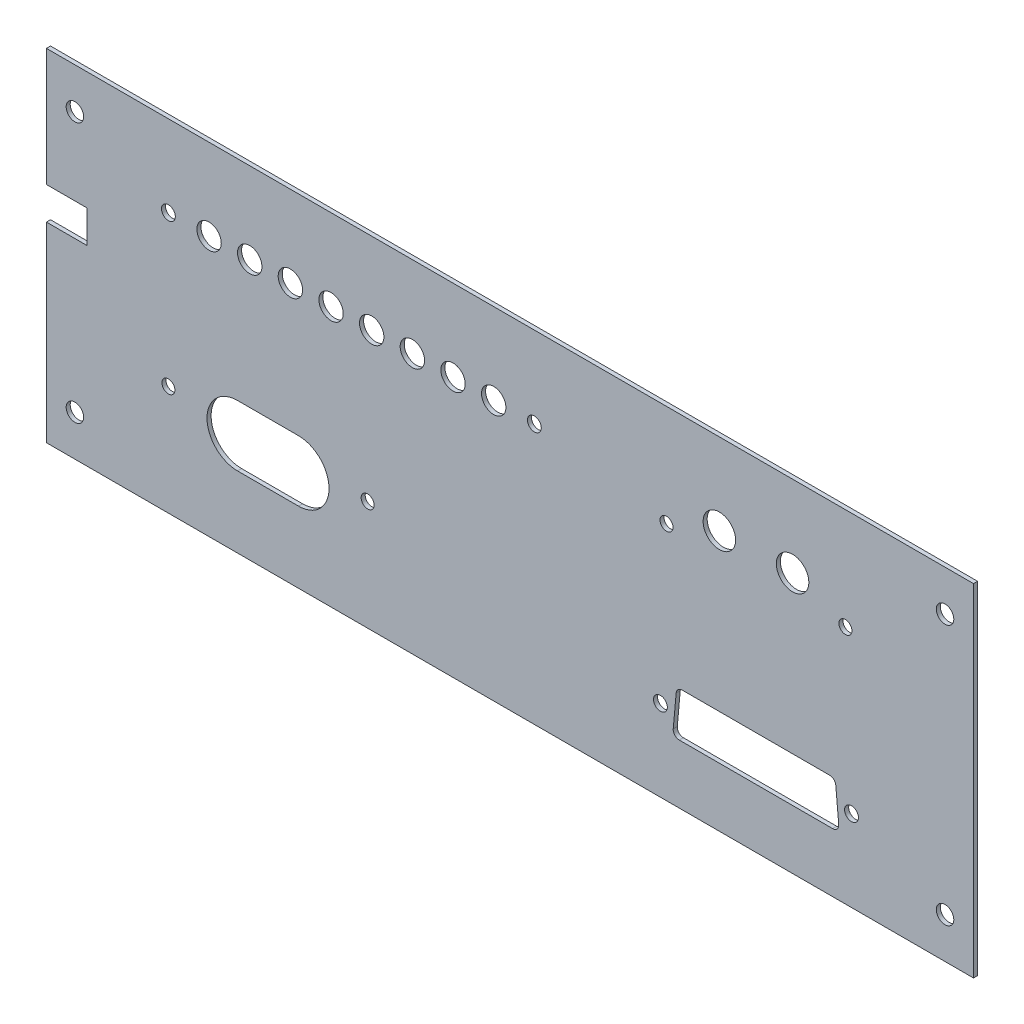
SolidWorks part; units mm, degrees
ref_plane "Спереди" through (0, 0, 0) normal (0, 0, 1) x (1, 0, 0)
ref_plane "Сверху" through (0, 0, 0) normal (0, 1, 0) x (1, 0, 0)
ref_plane "Справа" through (0, 0, 0) normal (1, 0, 0) x (0, 0, -1)
sketch "Эскиз1" plane through (0, 0, 0) normal (0, 0, 1) x (1, 0, 0)
  line L0 (0, 0) -> (58.061, 0) construction
  line L1 (0, 0) -> (0, 47.3035) construction
  line L3 (-114, -42) -> (114, -42)
  line L4 (-114, -42) -> (-114, 42)
  line L5 (-114, 42) -> (114, 42)
  line L6 (114, -42) -> (114, 42)
  circle A8 centre (107, 32) radius 2.15
  circle A9 centre (-107, 32) radius 2.15
  circle A10 centre (-107, -32) radius 2.15
  circle A11 centre (107, -32) radius 2.15
  dimension "D14" = 4.3
  dimension "D15" = 10
  dimension "D16" = 7
  dimension "D1" = 84
  dimension "D2" = 228
extrude "Вытянуть1" add sketch "Эскиз1" along normal blind 1
sketch "Эскиз3" plane through (0, 0, 1) normal (0, 0, 1) x (1, 0, 0)
  line L0 (-47.9981, -22) -> (120.6827, -22) construction
  line L1 (40.1487, -25.8642) -> (40.876, -17.8642)
  line L2 (41.6425, -27.5) -> (79.3575, -27.5)
  line L3 (-114, -42) -> (114, -42) construction
  line L4 (42.3698, -16.5) -> (78.6302, -16.5)
  line L5 (34.3104, 17) -> (86.5925, 17) construction
  line L6 (80.8513, -25.8642) -> (80.124, -17.8642)
  line L7 (60.5, 95.3032) -> (60.5, -77.6913) construction
  line L10 (51.5, 22) -> (68.5193, 22) construction
  line L11 (114, -42) -> (114, 42) construction
  line L12 (114, 42) -> (-114, 42) construction
  circle A0 centre (37, -22) radius 1.7
  circle A1 centre (84, -22) radius 1.7
  arc A2 (41.6425, -27.5) -> (40.1487, -25.8642) centre (41.6425, -26) cw
  arc A3 (42.3698, -16.5) -> (40.876, -17.8642) centre (42.3698, -18) ccw
  arc A4 (80.124, -17.8642) -> (78.6302, -16.5) centre (78.6302, -18) ccw
  arc A5 (79.3575, -27.5) -> (80.8513, -25.8642) centre (79.3575, -26) ccw
  circle A6 centre (38.5, 17) radius 1.6
  circle A7 centre (82.5, 17) radius 1.6
  circle A8 centre (51.5, 22) radius 4
  circle A9 centre (69.5, 22) radius 4
  point P14 (40, -27.5)
  point P17 (41, -16.5)
  point P20 (80, -16.5)
  point P23 (81, -27.5)
  dimension "D4" = 47
  dimension "D5" = 3.4
  dimension "D6" = 1.5
  dimension "D9" = 3.2
  dimension "D11" = 18
  dimension "D12" = 8
  dimension "D13" = 44
  dimension "D14" = 20
  dimension "D8" = 30
  dimension "D1" = 39
  dimension "D2" = 41
  dimension "D3" = 11
  dimension "D7" = 20
  dimension "D10" = 25
extrude "Вырез-Вытянуть1" cut sketch "Эскиз3" against normal blind 10
sketch "Эскиз4" plane through (0, 0, 1) normal (0, 0, 1) x (1, 0, 0)
  line L0 (-114, 42) -> (-114, -42) construction
  line L2 (-153.842, -17) -> (-33.1698, -17) construction
  line L6 (-67, -9.5) -> (-52, -9.5)
  line L7 (-67, -24.5) -> (-52, -24.5)
  line L8 (-59.5, -4.8658) -> (-59.5, -32.5755) construction
  line L9 (-108, 9) -> (-127.313, 9) construction
  line L10 (114, 42) -> (-114, 42) construction
  line L11 (-120.3986, 5) -> (-104, 5)
  line L12 (-120.3986, 5) -> (-120.3986, 13)
  line L13 (-120.3986, 13) -> (-104, 13)
  line L14 (-104, 5) -> (-104, 13)
  arc A5 (-67, -9.5) -> (-67, -24.5) centre (-67, -17) ccw
  arc A6 (-52, -9.5) -> (-52, -24.5) centre (-52, -17) cw
  circle A7 centre (-84, -15) radius 1.6
  circle A8 centre (-35, -15) radius 1.6
  dimension "D3" = 33
  dimension "D12" = 8
  dimension "D13" = 15
  dimension "D14" = 49
  dimension "D15" = 2
  dimension "D2" = 10
  dimension "D16" = 15
  dimension "D17" = 30
extrude "Вырез-Вытянуть2" cut sketch "Эскиз4" against normal blind 1
sketch "Эскиз5" plane through (0, 0, 1) normal (0, 0, 1) x (1, 0, 0)
  line L0 (-39, 37.0344) -> (-39, 0) construction
  line L1 (-84, 22) -> (6, 22) construction
  line L2 (114, 42) -> (-114, 42) construction
  line L3 (-114, 42) -> (-114, 13) construction
  circle A0 centre (-84, 22) radius 1.7
  circle A1 centre (6, 22) radius 1.7
  circle A2 centre (-4, 22) radius 3
  circle A3 centre (-14, 22) radius 3
  circle A4 centre (-24, 22) radius 3
  circle A5 centre (-34, 22) radius 3
  circle A6 centre (-44, 22) radius 3
  circle A7 centre (-54, 22) radius 3
  circle A8 centre (-64, 22) radius 3
  circle A9 centre (-74, 22) radius 3
  dimension "D1" = 90
  dimension "D2" = 3.4
  dimension "D5" = 6
  dimension "D3" = 20
  dimension "D4" = 30
  dimension "D6" = 35
extrude "Вырез-Вытянуть3" cut sketch "Эскиз5" against normal blind 10
